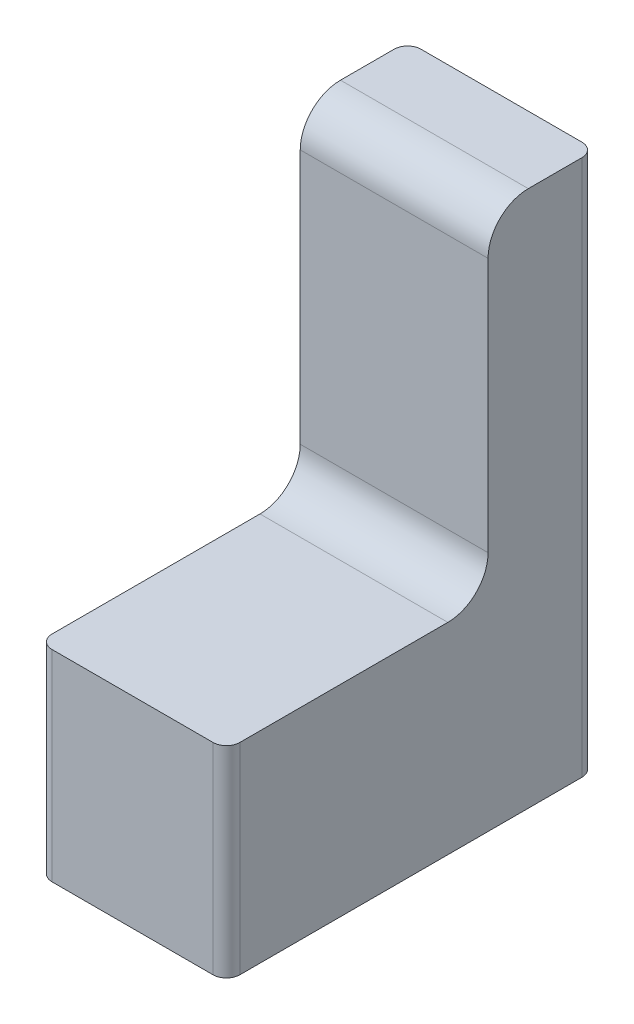
SolidWorks part; units mm, degrees
material "K110"
ref_plane "Front Plane" through (0, 0, 0) normal (0, 0, 1) x (1, 0, 0)
ref_plane "Top Plane" through (0, 0, 0) normal (0, 1, 0) x (1, 0, 0)
ref_plane "Right Plane" through (0, 0, 0) normal (1, 0, 0) x (0, 0, -1)
sketch "Sketch1" plane through (0, 0, 0) normal (0, 1, 0) x (1, 0, 0)
  line L1 (-7, -13.75) -> (7, -13.75)
  line L2 (-7, -13.75) -> (-7, 13.75)
  line L3 (-7, 13.75) -> (7, 13.75)
  line L4 (7, -13.75) -> (7, 13.75)
  line L5 (-7, -13.75) -> (7, 13.75) construction
  line L6 (-7, 13.75) -> (7, -13.75) construction
  point P0 (0, 0)
  dimension "D1" = 27.5
  dimension "D2" = 14
extrude "Boss-Extrude1" add sketch "Sketch1" against normal blind 40
sketch "Sketch2" plane through (7, 0, 0) normal (1, 0, 0) x (0, 0, -1)
  line L0 (13.75, -40) -> (13.75, 0) construction
  line L1 (-13.75, 0) -> (5.75, 0)
  line L2 (-13.75, 0) -> (-13.75, -25)
  line L3 (-13.75, -25) -> (5.75, -25)
  line L4 (5.75, 0) -> (5.75, -25)
  dimension "D1" = 25
  dimension "D2" = 8
extrude "Cut-Extrude1" cut sketch "Sketch2" against normal up to next
fillet "Fillet1" radius 3 2 edges at (0, -25, -5.75) (0, 0, -5.75)
hole_wizard "M6 Tapped Hole1" positions "Sketch8" profile "Sketch4" tap size "M6" standard "ISO"
sketch "Sketch8" plane through (0, -40, 0) normal (0, -1, 0) x (-1, 0, 0)
  line L0 (-7, 13.75) -> (7, 13.75) construction
  line L1 (7, -13.75) -> (-7, -13.75) construction
  point P0 (0, -7.75)
  point P2 (0, 7.75)
  dimension "D1" = 6
  dimension "D2" = 6
sketch "Sketch4" plane through (0, -40, 7.75) normal (1, 0, 0) x (0, 0, -1)
  line L0 (0, 0) -> (0, 13.5022)
  line L1 (0, 13.5022) -> (2.5, 12)
  line L2 (2.5, 12) -> (2.5, 0.525)
  line L3 (2.5, 0.525) -> (3.025, 0)
  line L5 (3.025, 0) -> (0, 0)
  line L6 (-2.5, 0.525) -> (-3.025, 0) construction
  line L10 (0, 13.5022) -> (-2.5, 12) construction
  line L11 (0, -6.35) -> (0, 107.95) construction
  dimension "Tap Drill Dia." = 5
  dimension "Tap Drill Depth" = 12
  dimension "Near C'Sink Dia." = 6.05
  dimension "Near C'Sink Angle" = 90
  dimension "Drill Angle" = 118
cosmetic thread "Hole Thread1"
cosmetic thread "Hole Thread2"
fillet "Fillet2" radius 1 4 edges at (-7, -20, -13.75) (7, -20, -13.75) (7, -32.5, 13.75) (-7, -32.5, 13.75)
